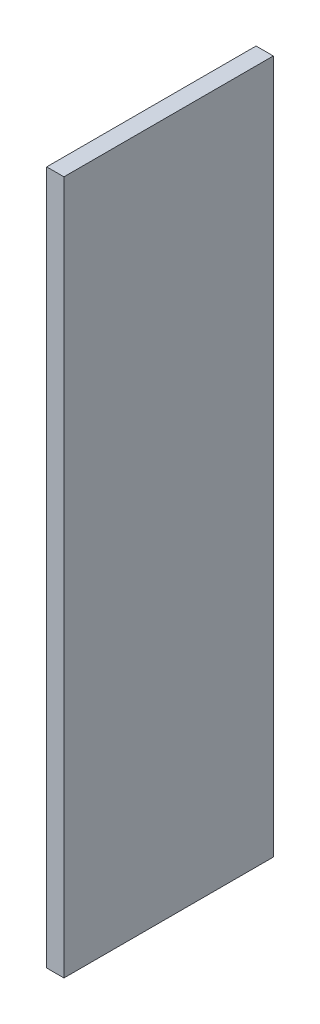
SolidWorks part; units mm, degrees
ref_plane "Front" through (0, 0, 0) normal (0, 0, 1) x (1, 0, 0)
ref_plane "Top" through (0, 0, 0) normal (0, 1, 0) x (1, 0, 0)
ref_plane "Right" through (0, 0, 0) normal (1, 0, 0) x (0, 0, -1)
sketch "Sketch1" plane through (0, 0, 0) normal (1, 0, 0) x (0, 0, -1)
  line L1 (111.125, -368.3) -> (-111.125, -368.3)
  line L2 (111.125, -368.3) -> (111.125, 368.3)
  line L3 (111.125, 368.3) -> (-111.125, 368.3)
  line L4 (-111.125, -368.3) -> (-111.125, 368.3)
  line L5 (111.125, -368.3) -> (-111.125, 368.3) construction
  line L6 (111.125, 368.3) -> (-111.125, -368.3) construction
  point P0 (0, 0)
  dimension "D1" = 222.25
  dimension "D2" = 736.6
extrude "Boss-Extrude1" add sketch "Sketch1" along normal blind 18.288
